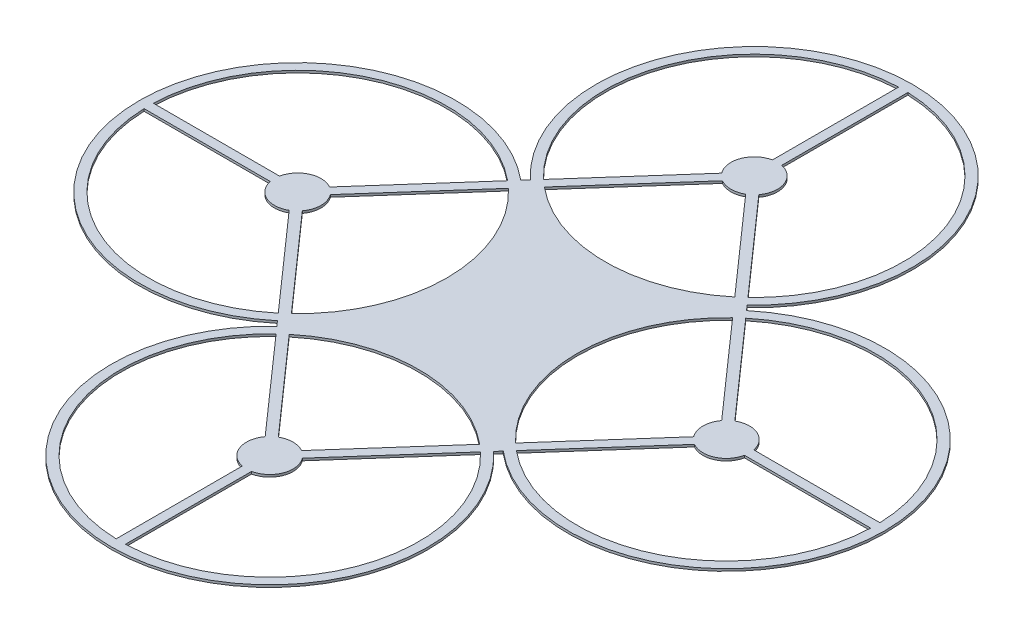
SolidWorks part; units mm, degrees
material "Thornel VCB-20 Carbon Cloth"
ref_plane "Front Plane" through (0, 0, 0) normal (0, 0, 1) x (1, 0, 0)
ref_plane "Top Plane" through (0, 0, 0) normal (0, 1, 0) x (1, 0, 0)
ref_plane "Right Plane" through (0, 0, 0) normal (1, 0, 0) x (0, 0, -1)
sketch "Sketch1" plane through (0, 0, 0) normal (0, 1, 0) x (1, 0, 0)
  line L0 (34.925, 231.4543) -> (34.925, 317.5)
  line L1 (28.575, 231.4543) -> (28.575, 317.5)
  line L2 (19.0661, 206.3536) -> (-37.9127, 141.9428)
  line L3 (23.8222, 202.1462) -> (-33.1566, 137.7354)
  line L4 (39.6778, 202.1462) -> (96.6566, 137.7354)
  line L5 (-49.3934, 128.9646) -> (-106.3722, 64.5538)
  line L6 (-129.8543, 53.975) -> (-215.9, 53.975)
  line L7 (-44.6373, 124.7572) -> (-101.6161, 60.3464)
  line L8 (193.3543, 47.625) -> (279.4, 47.625)
  line L9 (-42.122, 137.1845) -> (-45.1842, 133.7229)
  line L11 (193.3543, 53.975) -> (279.4, 53.975)
  line L12 (-129.8543, 47.625) -> (-215.9, 47.625)
  line L13 (105.622, 137.1845) -> (108.6842, 133.7229)
  line L14 (-106.3722, 37.0462) -> (-49.3934, -27.3646)
  line L15 (-101.6161, 41.2536) -> (-44.6373, -23.1572)
  line L16 (169.8722, 37.0462) -> (112.8934, -27.3646)
  line L18 (112.8934, 128.9646) -> (169.8722, 64.5538)
  line L19 (108.1373, 124.7572) -> (165.1161, 60.3464)
  line L20 (165.1161, 41.2536) -> (108.1373, -23.1572)
  line L21 (28.575, -129.8543) -> (28.575, -215.9)
  line L22 (96.6566, -36.1354) -> (39.6778, -100.5462)
  line L23 (101.4127, -40.3428) -> (44.4339, -104.7536)
  line L24 (44.4339, 206.3536) -> (101.4127, 141.9428)
  line L25 (34.925, -129.8543) -> (34.925, -215.9)
  line L27 (108.6842, -32.1229) -> (105.622, -35.5845)
  line L28 (-33.1566, -36.1354) -> (23.8222, -100.5462)
  line L29 (-37.9127, -40.3428) -> (19.0661, -104.7536)
  line L30 (-45.1842, -32.1229) -> (-42.122, -35.5845)
  arc A0 (-49.3934, 128.9646) -> (-215.8504, 53.975) centre (-114.3, 50.8) ccw
  arc A1 (279.3504, 53.975) -> (112.8934, 128.9646) centre (177.8, 50.8) ccw
  arc A2 (-37.9127, -40.3428) -> (28.575, -215.8504) centre (31.75, -114.3) ccw
  arc A3 (28.575, 317.4504) -> (-37.9127, 141.9428) centre (31.75, 215.9) ccw
  arc A5 (-45.1842, 133.7229) -> (-45.1842, -32.1229) centre (-114.3, 50.8) ccw
  arc A8 (28.575, 231.4543) -> (19.0661, 206.3536) centre (31.75, 215.9) ccw
  arc A9 (-129.8543, 47.625) -> (-106.3722, 37.0462) centre (-114.3, 50.8) ccw
  arc A10 (34.925, -129.8543) -> (44.4339, -104.7536) centre (31.75, -114.3) ccw
  arc A11 (165.1161, 60.3464) -> (165.1161, 41.2536) centre (177.8, 50.8) ccw
  arc A12 (23.8222, 202.1462) -> (39.6778, 202.1462) centre (31.75, 215.9) ccw
  arc A13 (44.4339, 206.3536) -> (34.925, 231.4543) centre (31.75, 215.9) ccw
  arc A14 (-33.1566, 137.7354) -> (96.6566, 137.7354) centre (31.75, 215.9) ccw
  arc A15 (101.4127, 141.9428) -> (34.925, 317.4504) centre (31.75, 215.9) ccw
  arc A16 (-44.6373, -23.1572) -> (-44.6373, 124.7572) centre (-114.3, 50.8) ccw
  arc A17 (-215.8504, 47.625) -> (-49.3934, -27.3646) centre (-114.3, 50.8) ccw
  arc A18 (-106.3722, 64.5538) -> (-129.8543, 53.975) centre (-114.3, 50.8) ccw
  arc A19 (-101.6161, 41.2536) -> (-101.6161, 60.3464) centre (-114.3, 50.8) ccw
  arc A20 (96.6566, -36.1354) -> (-33.1566, -36.1354) centre (31.75, -114.3) ccw
  arc A21 (34.925, -215.8504) -> (101.4127, -40.3428) centre (31.75, -114.3) ccw
  arc A22 (19.0661, -104.7536) -> (28.575, -129.8543) centre (31.75, -114.3) ccw
  arc A23 (39.6778, -100.5462) -> (23.8222, -100.5462) centre (31.75, -114.3) ccw
  arc A24 (193.3543, 53.975) -> (169.8722, 64.5538) centre (177.8, 50.8) ccw
  arc A25 (169.8722, 37.0462) -> (193.3543, 47.625) centre (177.8, 50.8) ccw
  arc A26 (112.8934, -27.3646) -> (279.3504, 47.625) centre (177.8, 50.8) ccw
  arc A27 (108.1373, 124.7572) -> (108.1373, -23.1572) centre (177.8, 50.8) ccw
  arc A28 (105.622, 137.1845) -> (-42.122, 137.1845) centre (31.75, 215.9) ccw
  arc A29 (108.6842, -32.1229) -> (108.6842, 133.7229) centre (177.8, 50.8) ccw
  arc A31 (-42.122, -35.5845) -> (105.622, -35.5845) centre (31.75, -114.3) ccw
extrude "Boss-Extrude2" add sketch "Sketch1" along normal blind 1.5748
